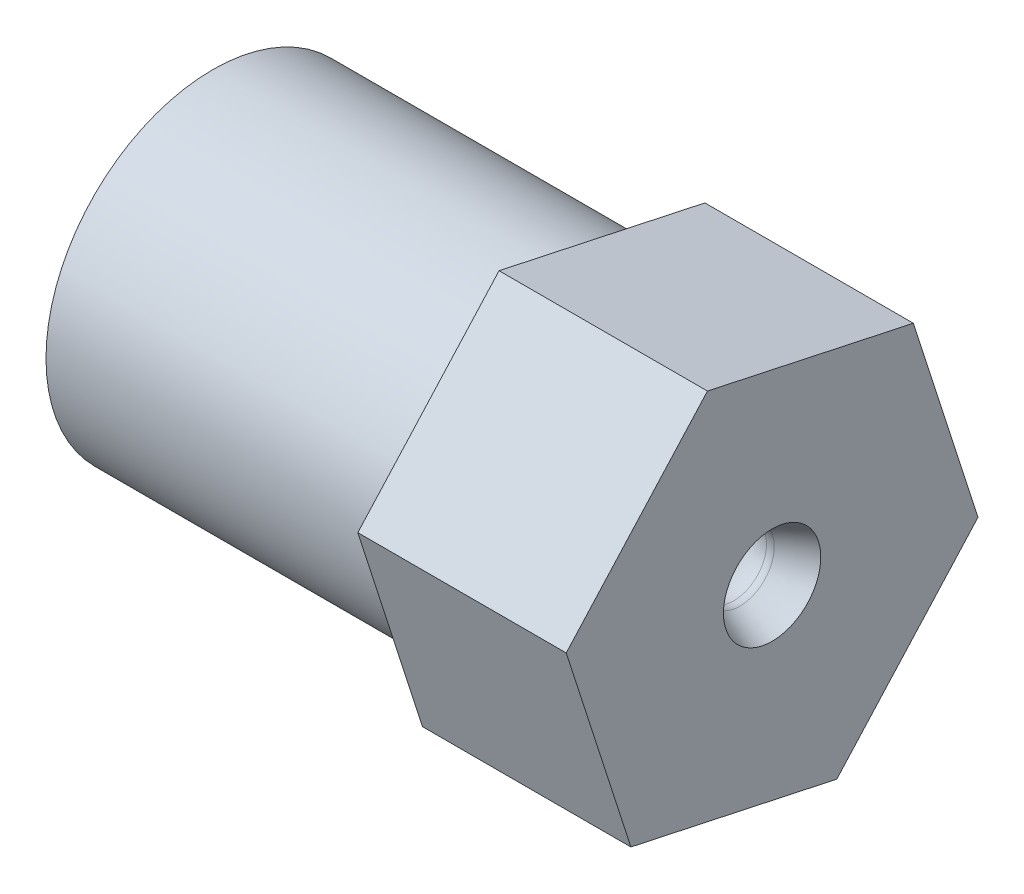
SolidWorks part; units mm, degrees
ref_plane "Front Plane" through (0, 0, 0) normal (0, 0, 1) x (1, 0, 0)
ref_plane "Top Plane" through (0, 0, 0) normal (0, 1, 0) x (1, 0, 0)
ref_plane "Right Plane" through (0, 0, 0) normal (1, 0, 0) x (0, 0, -1)
sketch "Sketch1" plane through (0, 0, 0) normal (0, 0, 1) x (1, 0, 0)
  line L0 (0, 0) -> (2.3378, 0) construction
  line L1 (0.3756, 2.0936) -> (2.3378, 3.137) construction
  line L2 (-2.1213, 2.8787) -> (-2.7577, 3.5151)
  line L3 (-31.75, 4.445) -> (-31.75, 10.16) construction
  line L4 (-5.0028, 4.445) -> (-31.75, 4.445) construction
  line L5 (-31.75, 10.16) -> (-10.3622, 10.16)
  line L6 (2.3378, 10.16) -> (2.3378, 2.9665)
  line L7 (2.3378, 2.9665) -> (12.3986, 6.6283) construction
  line L8 (-10.3622, 10.16) -> (2.3378, 10.16)
  line L9 (-5.0028, 4.445) -> (-13.462, 4.445)
  line L10 (-19.939, 5.461) -> (-19.939, 6.8199)
  line L11 (-20.066, 6.9469) -> (-24.892, 6.9469)
  line L12 (-24.892, 6.9469) -> (-24.892, 7.8994)
  line L13 (-25.019, 8.0264) -> (-31.115, 8.0264)
  line L14 (-31.75, 10.16) -> (-31.75, 8.6614)
  line L15 (0, 0) -> (-31.75, 0) construction
  line L16 (-13.462, 4.445) -> (-13.462, 4.699)
  line L17 (-13.589, 4.826) -> (-19.304, 4.826)
  arc A0 (-2.1213, 2.8787) -> (0, 2) centre (0, 5) ccw
  arc A1 (0, 2) -> (0.3756, 2.0936) centre (0, 2.8) ccw
  arc A2 (-2.7577, 3.5151) -> (-5.0028, 4.445) centre (-5.0028, 1.27) ccw
  arc A3 (-31.115, 8.0264) -> (-31.75, 8.6614) centre (-31.115, 8.6614) cw
  arc A4 (-19.304, 4.826) -> (-19.939, 5.461) centre (-19.304, 5.461) cw
  arc A5 (-13.462, 4.699) -> (-13.589, 4.826) centre (-13.589, 4.699) ccw
  arc A6 (-19.939, 6.8199) -> (-20.066, 6.9469) centre (-20.066, 6.8199) ccw
  arc A7 (-24.892, 7.8994) -> (-25.019, 8.0264) centre (-25.019, 7.8994) ccw
  parabola Q0 (2.3378, 2.9665) -> (0.3756, 2.0936) focus (3.9537, -4.6359) apex (0.3756, 2.0936)
  point P30 (-31.75, 8.0264)
  point P39 (-24.892, 8.0264)
  dimension "D3" = 3
  dimension "D4" = 0.8
  dimension "D11" = 3.175
  dimension "D12" = 20
  dimension "D14" = 6.9469
  dimension "D20" = 0.635
  dimension "D21" = 0.127
  dimension "D2" = 2.3378
  dimension "D5" = 2.9665
  dimension "D6" = 28
  dimension "D7" = 45
  dimension "D8" = 8.0264
  dimension "D9" = 31.75
  dimension "D10" = 10.16
  dimension "D13" = 12.7
  dimension "D15" = 4.445
  dimension "D16" = 6.858
  dimension "D17" = 11.811
  dimension "D18" = 18.288
  dimension "D19" = 4.826
  dimension "D22" = 2
revolve "Revolve1" add sketch "Sketch1" angle 360 about L0
sketch "Sketch4" plane through (2.3378, 0, 0) normal (1, 0, 0) x (0, 0, -1)
  line L1 (3.9404, -12.2116) -> (12.5458, -2.6933)
  line L2 (12.5458, -2.6933) -> (8.6054, 9.5183)
  line L3 (8.6054, 9.5183) -> (-3.9404, 12.2116)
  line L4 (-3.9404, 12.2116) -> (-12.5458, 2.6933)
  line L5 (-12.5458, 2.6933) -> (-8.6054, -9.5183)
  line L6 (-8.6054, -9.5183) -> (3.9404, -12.2116)
  circle A0 centre (0, 0) radius 10.16
  circle A1 centre (0, 0) radius 10.16 construction
  circle A2 centre (0, 0) radius 11.1125 construction
  circle M1 centre (0, 0) radius 10.16
  dimension "D1" = 22.225
extrude "Boss-Extrude1" add sketch "Sketch4" against normal blind 12.7 contours L4 L5 M1 | L3 L4 M1 | L2 L3 M1 | L1 L2 M1 | L6 L1 M1 | L5 L6 M1
fillet "Fillet1" radius 0.635 1 edges at (-10.3622, 0, -10.16)
equation "\"D3@Sketch1\" = 1.5 * \"D22@Sketch1\""
equation "\"D4@Sketch1\"  = .4 * \"D22@Sketch1\""
equation "\"D5@Sketch1\"=\"D22@Sketch1\" * ( \"er\") ^ .5"
equation "\"er\"= 2.2"
